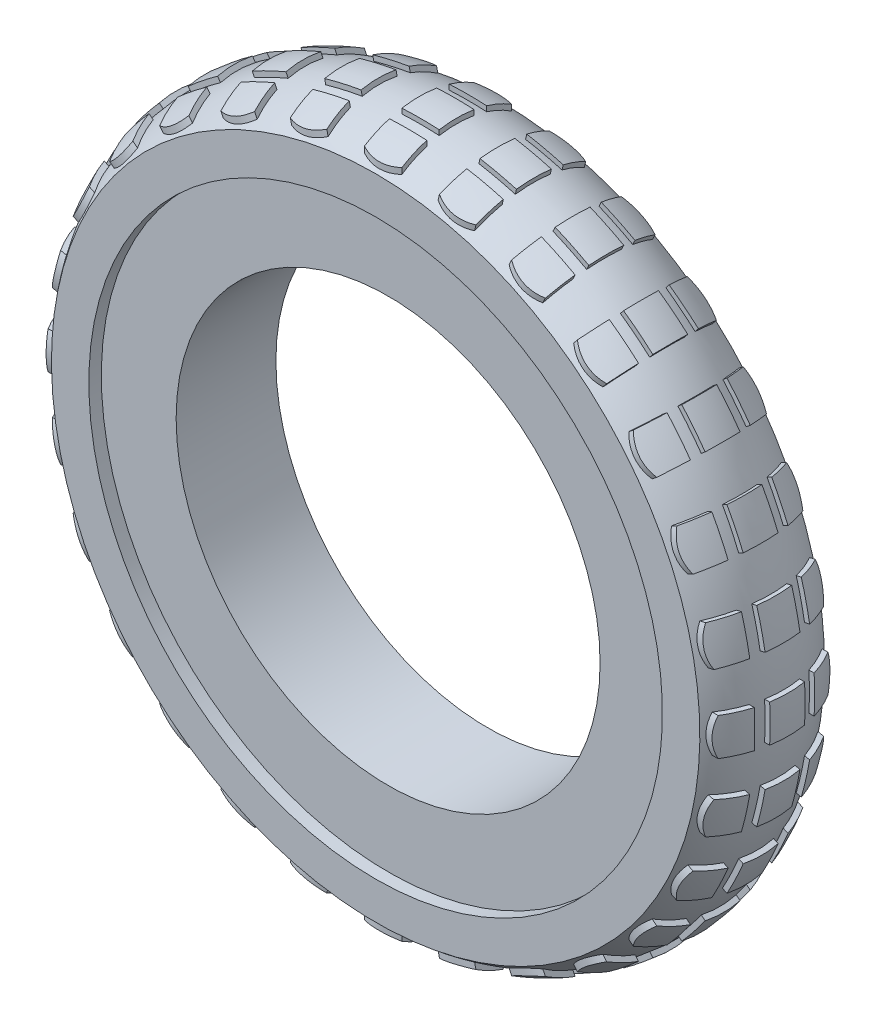
SolidWorks part; units mm, degrees
ref_plane "前基準面" through (0, 0, 0) normal (0, 0, 1) x (1, 0, 0)
ref_plane "上基準面" through (0, 0, 0) normal (0, 1, 0) x (1, 0, 0)
ref_plane "右基準面" through (0, 0, 0) normal (1, 0, 0) x (0, 0, -1)
sketch "草圖1" plane through (0, 0, 0) normal (0, 0, 1) x (1, 0, 0)
  circle A0 centre (0, 0) radius 8.5
  circle A1 centre (0, 0) radius 11.5
  dimension "D1" = 17
  dimension "D2" = 3
extrude "填料-伸長1" add sketch "草圖1" along normal blind 4
sketch "草圖3" plane through (0, 0, 0) normal (1, 0, 0) x (0, 0, -1)
  line L0 (0, 0) -> (-2, 0) construction
  line L1 (-4.5, 11.5) -> (0.5, 11.5)
  line L2 (-4.5, 11.5) -> (-4.5, 13)
  line L3 (-4.5, 13) -> (0.5, 13)
  line L4 (0.5, 11.5) -> (0.5, 13)
  line L5 (-2, 0) -> (-2, -11.5) construction
  line L6 (-4, -11.5) -> (0, -11.5) construction
  line L7 (-2, 0) -> (-2, 13) construction
  arc A0 (-4.5, 13) -> (0.5, 13) centre (-2, 9.8775) cw
  dimension "D4" = 4
  dimension "D1" = 11.5
  dimension "D2" = 1.5
  dimension "D3" = 5
revolve "旋轉1" add sketch "草圖3" angle 360 about L0
sketch "草圖4" plane through (0, 0, 0) normal (0, 1, 0) x (1, 0, 0)
  line L0 (0, 0.5) -> (0, -4.5) construction
  line L5 (11.5, 0.5) -> (-11.5, 0.5) construction
  line L6 (-13, -4.5) -> (13, -4.5) construction
  line L7 (0, -2) -> (-1.8514, -2) construction
  line L8 (-0.75, -2.7) -> (0.75, -2.7)
  line L9 (-0.75, -2.7) -> (-0.75, -1.3)
  line L10 (-0.75, -1.3) -> (0.75, -1.3)
  line L11 (0.75, -2.7) -> (0.75, -1.3)
  line L12 (-0.75, -2.7) -> (0.75, -1.3) construction
  line L13 (-0.75, -1.3) -> (0.75, -2.7) construction
  line L14 (-0.75, -0.8) -> (0.75, -0.8)
  line L15 (-0.75, -0.8) -> (-0.75, 0.2)
  line L16 (-0.75, 0.2) -> (0.75, 0.2) construction
  line L17 (0.75, -0.8) -> (0.75, 0.2)
  line L18 (-0.75, -0.8) -> (0.75, 0.2) construction
  line L19 (-0.75, 0.2) -> (0.75, -0.8) construction
  line L20 (0.75, -3.2) -> (0.75, -4.2)
  line L21 (-0.75, -3.2) -> (0.75, -3.2)
  line L22 (-0.75, -3.2) -> (-0.75, -4.2)
  arc A0 (-0.75, 0.2) -> (0.75, 0.2) centre (0, -1.4363) cw
  arc A1 (-0.75, -4.2) -> (0.75, -4.2) centre (0, -2.5637) ccw
  point P0 (0, -2)
  point P11 (0, -0.3)
  dimension "D5" = 1.8
  dimension "D1" = 1.4
  dimension "D2" = 1.5
  dimension "D3" = 1.5
  dimension "D4" = 1
  dimension "D6" = 1.2
extrude "填料-伸長2" add sketch "草圖4" along normal offset from surface (1.9987 mm away) 0.2 from offset 12
pattern_circular "環狀複製排列1" count 28 over 360 about axis through (0, 0, 0) along (0, 0, 1) of "填料-伸長2"
